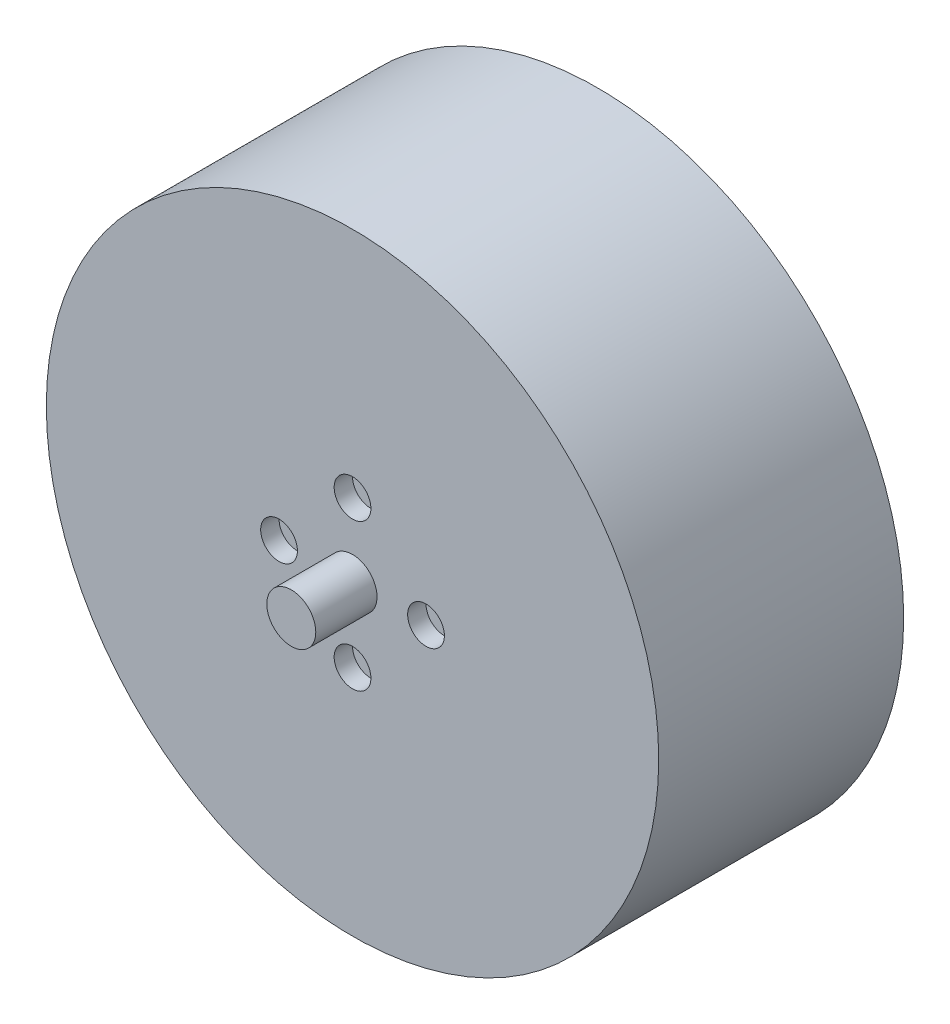
SolidWorks part; units mm, degrees
ref_plane "Front Plane" through (0, 0, 0) normal (1, 0, 0) x (0, 1, 0)
ref_plane "Top Plane" through (0, 0, 0) normal (0, 0, 1) x (0, 1, 0)
ref_plane "Right Plane" through (0, 0, 0) normal (0, 1, 0) x (-1, 0, 0)
sketch "Sketch1" plane through (0, 0, 0) normal (0, 0, 1) x (0, 1, 0)
  line L0 (-8, 0) -> (8, 0) construction
  line L1 (0, 9.5) -> (0, -9.5) construction
  circle A0 centre (0, 0) radius 12.5
  circle A1 centre (0, 9.5) radius 1.5
  circle A2 centre (-8, 0) radius 1.5
  circle A3 centre (8, 0) radius 1.5
  circle A4 centre (0, -9.5) radius 1.5
  point P11 (0, 0)
  point P12 (0, 0)
  dimension "D1" = 25
  dimension "D2" = 3
  dimension "D3" = 16
  dimension "D4" = 19
extrude "Boss-Extrude1" add sketch "Sketch1" along normal blind 4
sketch "Sketch2" plane through (0, 0, 4) normal (0, 0, 1) x (1, 0, 0)
  circle A0 centre (0, 0) radius 5
  dimension "D1" = 10
extrude "Boss-Extrude2" add sketch "Sketch2" along normal blind 3
sketch "Sketch3" plane through (0, 0, 7) normal (0, 0, 1) x (1, 0, 0)
  circle A0 centre (0, 0) radius 25
  dimension "D1" = 50
extrude "Boss-Extrude3" add sketch "Sketch3" along normal blind 20
sketch "Sketch4" plane through (0, 0, 27) normal (0, 0, 1) x (1, 0, 0)
  circle A0 centre (0, 6) radius 1.5
  circle A1 centre (6, 0) radius 1.5
  circle A2 centre (0, -6) radius 1.5
  circle A3 centre (-6, 0) radius 1.5
  point P2 (6.6141, -3.7698)
  point P4 (0, 0)
  point P12 (0, 0)
  dimension "D1" = 3
  dimension "D2" = 6
  dimension "D3" = 4
extrude "Cut-Extrude1" cut sketch "Sketch4" against normal mid plane 3
sketch "Sketch5" plane through (0, 0, 27) normal (0, 0, 1) x (1, 0, 0)
  circle A0 centre (0, 0) radius 2
  dimension "D1" = 4
extrude "Boss-Extrude4" add sketch "Sketch5" along normal blind 5
sketch "Sketch6" plane through (0, 0, 0) normal (0, 0, -1) x (1, 0, 0)
  circle A0 centre (0, 0) radius 5.5
  dimension "D1" = 11
extrude "Cut-Extrude2" cut sketch "Sketch6" against normal mid plane 3
sketch "Sketch7" plane through (0, 0, 1.5) normal (0, 0, -1) x (1, 0, 0)
  circle A0 centre (0, 0) radius 1.5
  dimension "D1" = 3
extrude "Cut-Extrude3" cut sketch "Sketch7" against normal blind 5
